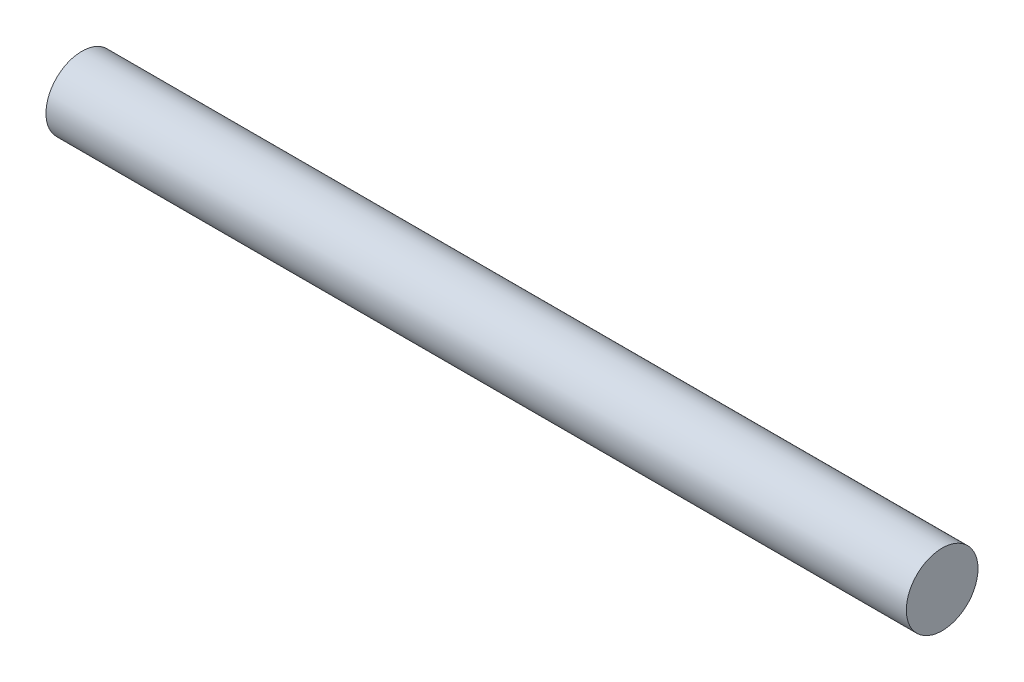
SolidWorks part; units mm, degrees
ref_plane "Plano frontal" through (0, 0, 0) normal (0, 0, 1) x (1, 0, 0)
ref_plane "Plano superior" through (0, 0, 0) normal (0, 1, 0) x (1, 0, 0)
ref_plane "Plano direito" through (0, 0, 0) normal (1, 0, 0) x (0, 0, -1)
sketch "Esboço1" plane through (0, 0, 0) normal (1, 0, 0) x (0, 0, -1)
  circle A0 centre (0, 0) radius 0.5
  dimension "D1" = 1
extrude "Ressalto-extrusão1" add sketch "Esboço1" along normal blind 12
